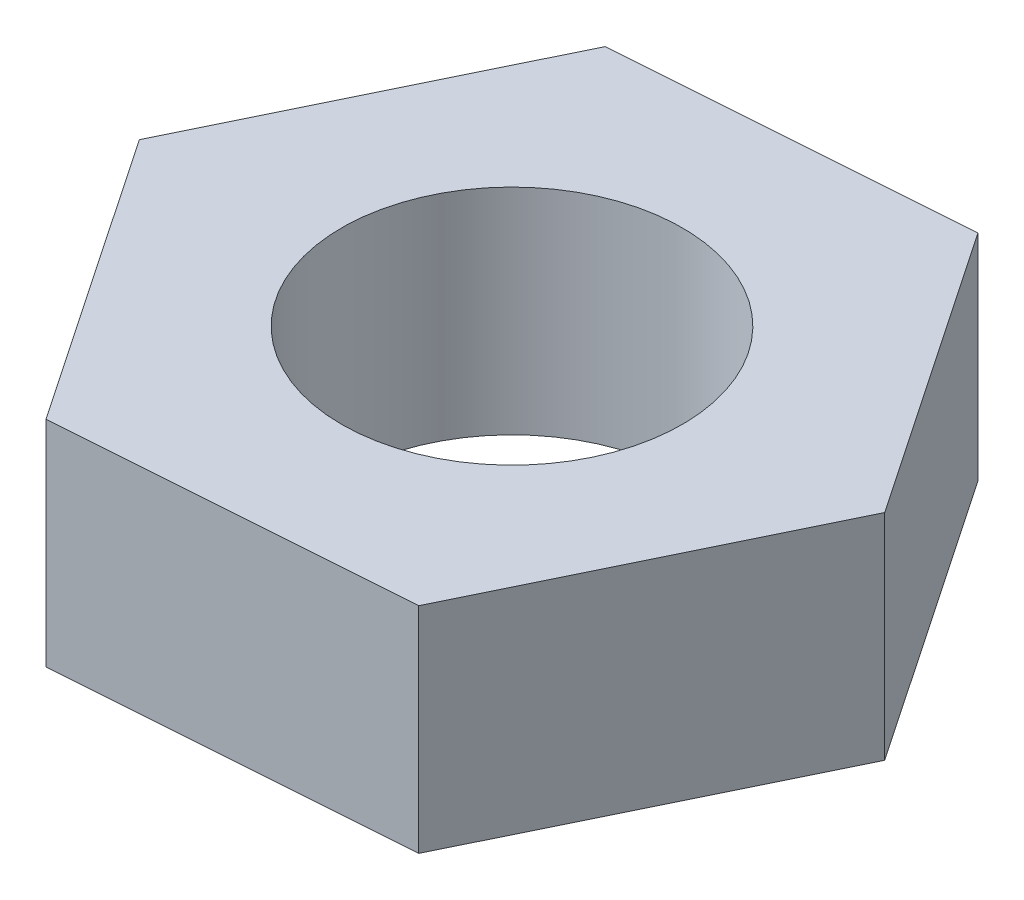
SolidWorks part; units mm, degrees
material "AISI 316 Stainless Steel Sheet (SS)"
ref_plane "Front Plane" through (0, 0, 0) normal (0, 0, 1) x (1, 0, 0)
ref_plane "Top Plane" through (0, 0, 0) normal (0, 1, 0) x (1, 0, 0)
ref_plane "Right Plane" through (0, 0, 0) normal (1, 0, 0) x (0, 0, -1)
sketch "Sketch1" plane through (0, 0, 0) normal (0, 1, 0) x (1, 0, 0)
  line L1 (7.287, -10.7657) -> (12.9668, 0.9279)
  line L2 (12.9668, 0.9279) -> (5.6799, 11.6935)
  line L3 (5.6799, 11.6935) -> (-7.287, 10.7657)
  line L4 (-7.287, 10.7657) -> (-12.9668, -0.9279)
  line L5 (-12.9668, -0.9279) -> (-5.6799, -11.6935)
  line L6 (-5.6799, -11.6935) -> (7.287, -10.7657)
  circle A0 centre (0, 0) radius 11.2583 construction
  circle A1 centre (0, 0) radius 6.35
  dimension "D2" = 12.7
  dimension "D1" = 13
extrude "Boss-Extrude1" add sketch "Sketch1" along normal blind 8
equation "\"innerDiameter\"= 1in / 2"
equation "\"D2@Sketch1\"=\"innerDiameter\""
